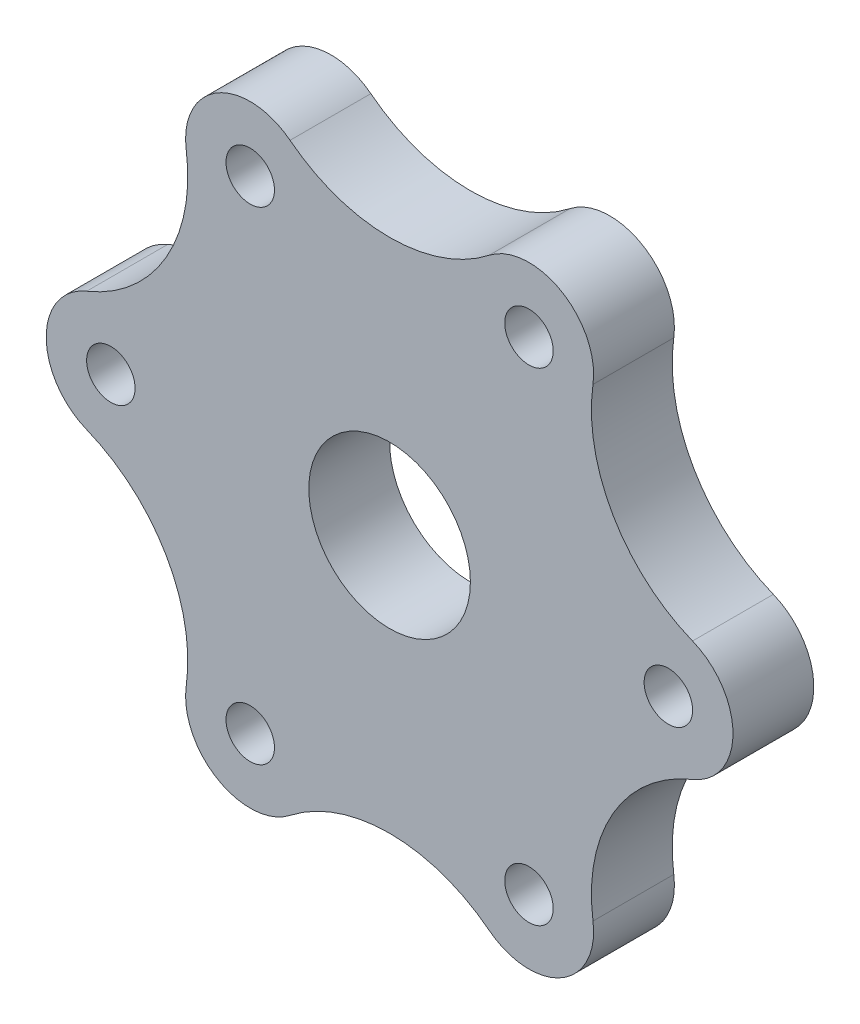
SolidWorks part; units mm, degrees
ref_plane "Front Plane" through (0, 0, 0) normal (0, 0, 1) x (1, 0, 0)
ref_plane "Top Plane" through (0, 0, 0) normal (0, 1, 0) x (1, 0, 0)
ref_plane "Right Plane" through (0, 0, 0) normal (1, 0, 0) x (0, 0, -1)
sketch "Sketch2" plane through (0, 0, 0) normal (0, 0, 1) x (1, 0, 0)
  circle A0 centre (0, 0) radius 10
  circle A1 centre (0, 0) radius 34.5 construction
  circle A2 centre (-34.5, 0) radius 3
  circle A3 centre (-17.25, 29.8779) radius 3
  circle A4 centre (17.25, 29.8779) radius 3
  circle A5 centre (34.5, 0) radius 3
  circle A6 centre (17.25, -29.8779) radius 3
  circle A7 centre (-17.25, -29.8779) radius 3
  arc A8 (-37.493, 7.419) -> (-37.493, -7.419) centre (-34.5, 0) ccw
  arc A9 (-12.3214, 36.1794) -> (-25.1716, 28.7604) centre (-17.25, 29.8779) ccw
  arc A10 (25.1716, 28.7604) -> (12.3214, 36.1794) centre (17.25, 29.8779) ccw
  arc A11 (37.493, -7.419) -> (37.493, 7.419) centre (34.5, 0) ccw
  arc A12 (12.3214, -36.1794) -> (25.1716, -28.7604) centre (17.25, -29.8779) ccw
  arc A13 (-25.1716, -28.7604) -> (-12.3214, -36.1794) centre (-17.25, -29.8779) ccw
  arc A14 (-37.493, 7.419) -> (-25.1716, 28.7604) centre (-44.9755, 25.9666) ccw
  arc A15 (-12.3214, 36.1794) -> (12.3214, 36.1794) centre (0, 51.9332) ccw
  arc A16 (25.1716, 28.7604) -> (37.493, 7.419) centre (44.9755, 25.9666) ccw
  arc A17 (37.493, -7.419) -> (25.1716, -28.7604) centre (44.9755, -25.9666) ccw
  arc A18 (12.3214, -36.1794) -> (-12.3214, -36.1794) centre (0, -51.9332) ccw
  arc A19 (-25.1716, -28.7604) -> (-37.493, -7.419) centre (-44.9755, -25.9666) ccw
  point P18 (0, 0)
  point P30 (0, 0)
  point P49 (0, 0)
  dimension "D1" = 20
  dimension "D2" = 69
  dimension "D3" = 6
  dimension "D4" = 16
  dimension "D7" = 20
  dimension "D5" = 6
  dimension "D6" = 6
  dimension "D8" = 6
extrude "Boss-Extrude1" add sketch "Sketch2" along normal mid plane 10
